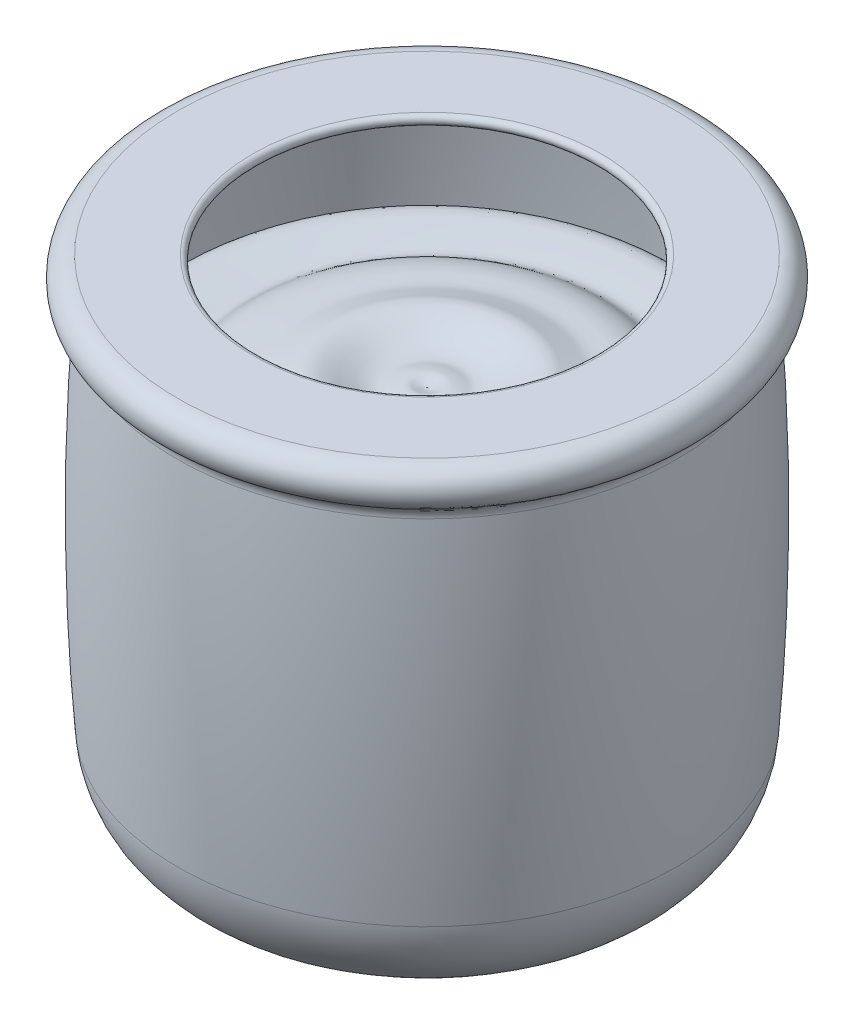
SolidWorks part; units mm, degrees
ref_plane "Ön Düzlem" through (0, 0, 0) normal (0, 0, 1) x (1, 0, 0)
ref_plane "Üst Düzlem" through (0, 0, 0) normal (0, 1, 0) x (1, 0, 0)
ref_plane "Sağ Düzlem" through (0, 0, 0) normal (1, 0, 0) x (0, 0, -1)
sketch "Çizim1" plane through (0, 0, 0) normal (0, 0, 1) x (1, 0, 0)
  line L0 (0, 0) -> (0, -100) construction
  line L1 (0, -100) -> (-30, -100)
  line L2 (-50, 0) -> (-35, 0)
  line L3 (-50, 0) -> (0, 0) construction
  line L4 (0, -98) -> (-30, -98)
  line L5 (-50, -2) -> (-35, -2)
  line L6 (0, -98) -> (0, -100)
  arc A0 (-50.1724, -10.4469) -> (-49.9448, -81.4847) centre (448.6756, -44.3679) ccw
  arc A1 (-50, 0) -> (-51.8089, -7.5676) centre (-50, -4) ccw
  arc A2 (-49.9448, -81.4847) -> (-30, -100) centre (-30, -80) ccw
  arc A3 (-51.8089, -7.5676) -> (-50.1724, -10.4469) centre (-53.1655, -10.2434) cw
  arc A4 (-47.9503, -81.3362) -> (-30, -98) centre (-30, -80) ccw
  arc A5 (-48.177, -10.5826) -> (-47.9503, -81.3362) centre (448.6756, -44.3679) ccw
  arc A6 (-50.9044, -5.7838) -> (-48.177, -10.5826) centre (-53.1655, -10.2434) cw
  arc A7 (-50, -2) -> (-50.9044, -5.7838) centre (-50, -4) ccw
  arc A8 (-35, 0) -> (-35, -2) centre (-35, -1) cw
  point P19 (-50, -8)
  dimension "D4" = 20
  dimension "D5" = 500
  dimension "D3" = 4
  dimension "D8" = 3
  dimension "D1" = 100
  dimension "D2" = 50
  dimension "D6" = 30
  dimension "D7" = 15
  dimension "D9" = 2
revolve "Döndür1" add sketch "Çizim1" angle 360 about L0
sketch "Çizim2" plane through (0, 0, 0) normal (0, 0, 1) x (1, 0, 0)
  line L1 (0, 0) -> (0, -100) construction
  line L2 (0, -23.0146) -> (0, -98)
  line L3 (0, -98) -> (-30, -98)
  line L5 (-47.9503, -81.3362) -> (47.9503, -81.3362) construction
  line L6 (30, -98) -> (-30, -98) construction
  arc A0 (-30, -98) -> (-47.9503, -81.3362) centre (-30, -80) cw
  arc A1 (-47.9503, -81.3362) -> (-49.2737, -51.4729) centre (448.6756, -44.3679) cw
  arc A2 (-48.177, -10.5826) -> (-47.9503, -81.3362) centre (448.6756, -44.3679) ccw construction
  spline S0 degree 3 poles (-49.2737, -51.4729) (-52.0022, -39.395) (-28.8134, -26.3541) (-51.6997, -35.2177) (-50.3131, -21.6639) (-36.8161, -27.4412) (-34.0997, -23.7152) (-28.4261, -22.1743) (-22.8219, -22.6134) (-16.6824, -18.6765) (-11.3127, -22.525) (-6.0407, -23.4804) (-2.8062, -21.5826) (-0.1362, -23.6344) (0, -23.0146) knots 0 0 0 0 0.213885 0.246678 0.327935 0.403879 0.467501 0.559411 0.637708 0.717662 0.850741 0.888841 0.950999 1 1 1 1
revolve "Döndür2" add sketch "Çizim2" angle 360 about L2
